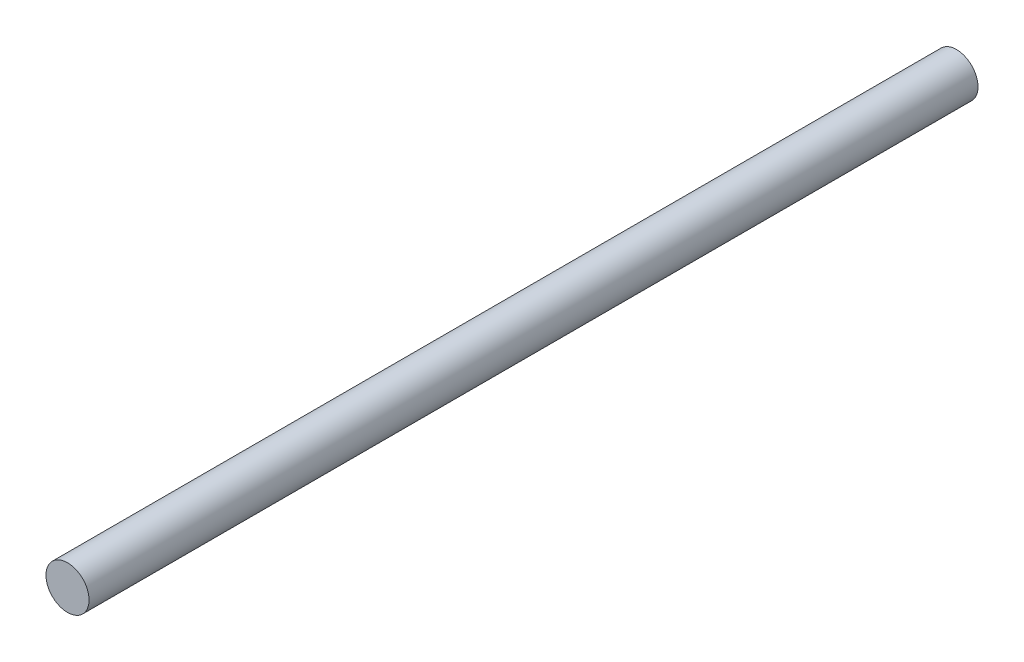
SolidWorks part; units mm, degrees
material "1.4000 (X6Cr13)"
ref_plane "Plan de face" through (0, 0, 0) normal (0, 0, 1) x (1, 0, 0)
ref_plane "Plan de dessus" through (0, 0, 0) normal (0, 1, 0) x (1, 0, 0)
ref_plane "Plan de droite" through (0, 0, 0) normal (1, 0, 0) x (0, 0, -1)
sketch "Esquisse1" plane through (0, 0, 0) normal (0, 0, 1) x (1, 0, 0)
  circle A0 centre (0, 0) radius 4
extrude "Boss.-Extru.1" add sketch "Esquisse1" along normal blind 165
ref_plane "SectionMiBarreY" through (0, 0, 82.5) normal (0, 0, -1) x (-1, 0, 0)
